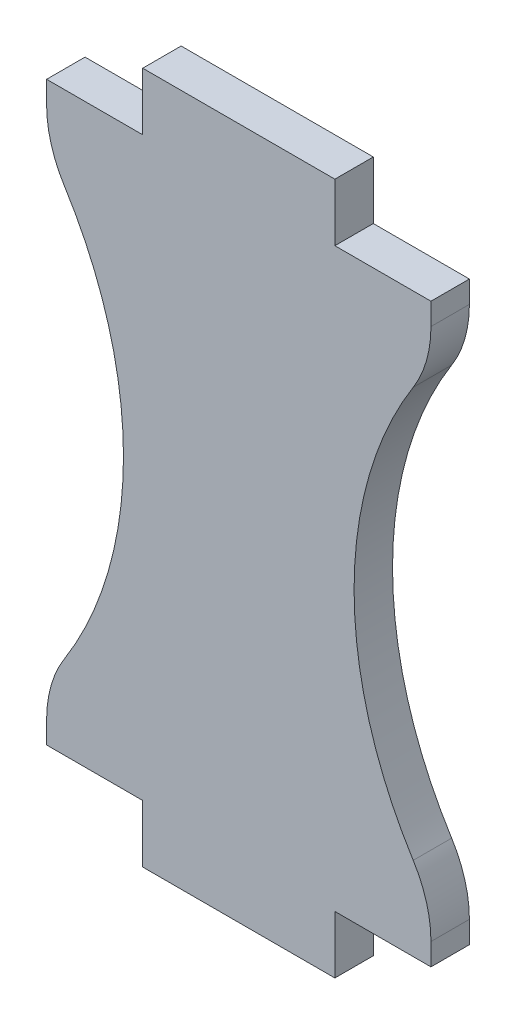
SolidWorks part; units mm, degrees
ref_plane "Спереди" through (0, 0, 0) normal (0, 0, 1) x (1, 0, 0)
ref_plane "Сверху" through (0, 0, 0) normal (0, 1, 0) x (1, 0, 0)
ref_plane "Справа" through (0, 0, 0) normal (1, 0, 0) x (0, 0, -1)
sketch "Model" plane through (0, 0, 0) normal (0, 0, 1) x (1, 0, 0)
  line L0 (-10, 33) -> (-5, 33)
  line L1 (-5, 33) -> (-5, 36)
  line L2 (-5, 36) -> (5, 36)
  line L3 (5, 36) -> (5, 33)
  line L4 (5, 33) -> (10, 33)
  line L5 (10, 33) -> (10, 31.8564)
  line L6 (10, 4.1436) -> (10, 3)
  line L7 (10, 3) -> (5, 3)
  line L8 (5, 3) -> (5, 0)
  line L9 (5, 0) -> (-5, 0)
  line L10 (-5, 0) -> (-5, 3)
  line L11 (-5, 3) -> (-10, 3)
  line L12 (-10, 3) -> (-10, 4.1436)
  line L13 (-10, 31.8564) -> (-10, 33)
  arc A0 (9.0769, 28.6588) -> (10, 31.8564) centre (4, 31.8564) ccw
  arc A1 (9.0769, 28.6588) -> (9.0769, 7.3412) centre (26, 18) ccw
  arc A2 (10, 4.1436) -> (9.0769, 7.3412) centre (4, 4.1436) ccw
  arc A3 (-9.0769, 7.3412) -> (-10, 4.1436) centre (-4, 4.1436) ccw
  arc A4 (-9.0769, 7.3412) -> (-9.0769, 28.6588) centre (-26, 18) ccw
  arc A5 (-10, 31.8564) -> (-9.0769, 28.6588) centre (-4, 31.8564) ccw
extrude "Бобышка-Вытянуть1" add sketch "Model" along normal blind 2
